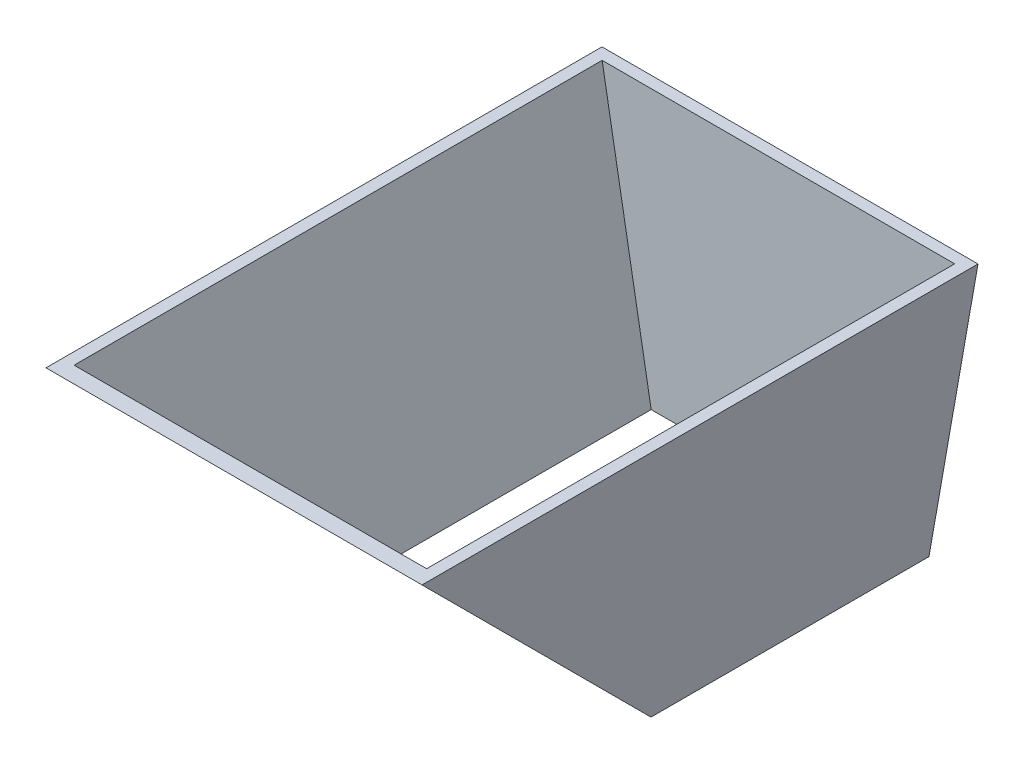
SolidWorks part; units mm, degrees
ref_plane "Front Plane" through (0, 0, 0) normal (0, 0, 1) x (1, 0, 0)
ref_plane "Top Plane" through (0, 0, 0) normal (0, 1, 0) x (1, 0, 0)
ref_plane "Right Plane" through (0, 0, 0) normal (1, 0, 0) x (0, 0, -1)
sketch "Sketch1" plane through (0, 0, 0) normal (0, 0, 1) x (1, 0, 0)
  line L0 (-40.5796, 30) -> (40.5796, 30)
  line L1 (40.5796, 30) -> (30, -30)
  line L2 (30, -30) -> (-30, -30)
  line L3 (-30, -30) -> (-40.5796, 30)
  line L4 (-30, -30) -> (-30, -23.0721) construction
  point P0 (0, -30)
  point P3 (0, 30)
  point P6 (35.2898, 0)
  dimension "D1" = 60
  dimension "D2" = 10
  dimension "D3" = 60
extrude "Boss-Extrude1" add sketch "Sketch1" along normal blind 120
sketch "Sketch2" plane through (0, 0, 0) normal (1, 0, 0) x (0, 0, -1)
  line L0 (-120, 30) -> (-120, -30)
  line L1 (-120, -30) -> (-60, -30)
  line L2 (-120, -30) -> (0, -30) construction
  line L3 (-60, -30) -> (-120, 30)
  dimension "D1" = 60
extrude "Cut-Extrude1" cut sketch "Sketch2" against normal through all both and the other way through all
shell "Shell1" thickness 2.5
